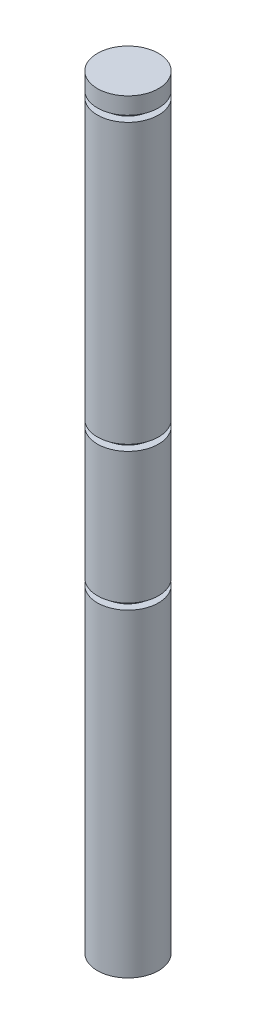
SolidWorks part; units mm, degrees
ref_plane "Front Plane" through (0, 0, 0) normal (0, 0, 1) x (1, 0, 0)
ref_plane "Top Plane" through (0, 0, 0) normal (0, 1, 0) x (1, 0, 0)
ref_plane "Right Plane" through (0, 0, 0) normal (1, 0, 0) x (0, 0, -1)
sketch "Sketch1" plane through (0, 0, 0) normal (0, 1, 0) x (1, 0, 0)
  circle A0 centre (0, 0) radius 4
  dimension "D1" = 8
extrude "Boss-Extrude1" add sketch "Sketch1" along normal blind 100
sketch "Sketch2" plane through (0, 0, 0) normal (1, 0, 0) x (0, 0, -1)
  line L0 (0, 100) -> (0, 84.2493) construction
  line L1 (4, 100) -> (-4, 100) construction
  line L2 (4, 0) -> (4, 100) construction
  line L3 (4, 97.8) -> (3, 97.8)
  line L4 (4, 97.8) -> (4, 97)
  line L5 (4, 97) -> (3, 97)
  line L6 (3, 97.8) -> (3, 97)
  dimension "D1" = 0.8
  dimension "D2" = 1
  dimension "D3" = 3
revolve "Cut-Revolve1" cut sketch "Sketch2" angle 360 about L0
sketch "Sketch3" plane through (0, 0, 0) normal (1, 0, 0) x (0, 0, -1)
  line L0 (4, 0) -> (4, 97) construction
  line L1 (4, 59.7) -> (3, 59.7)
  line L2 (4, 59.7) -> (4, 60.5)
  line L3 (4, 60.5) -> (3, 60.5)
  line L4 (3, 59.7) -> (3, 60.5)
  line L6 (0, 100) -> (0, 36.3763) construction
  line L7 (4, 100) -> (-4, 100) construction
  dimension "D1" = 0.8
  dimension "D2" = 60.5
  dimension "D3" = 1
revolve "Cut-Revolve2" cut sketch "Sketch3" angle 360 about L6
pattern_linear "LPattern1" count 2 spacing 18 along (0, -1, 0) of "Cut-Revolve2"
